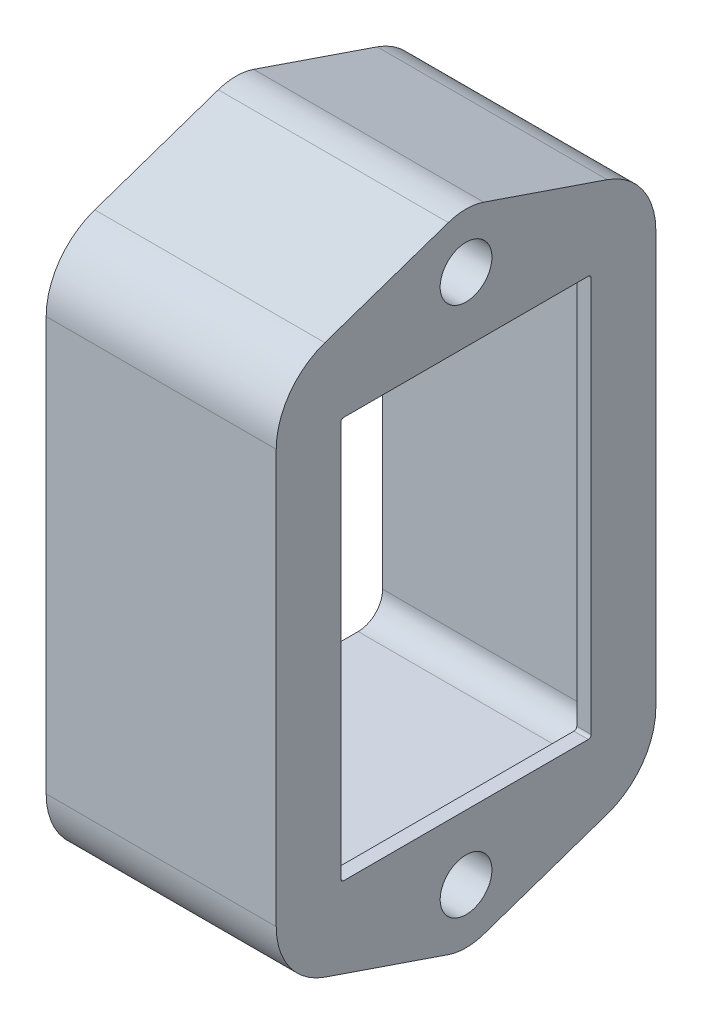
SolidWorks part; units mm, degrees
ref_plane "Alzado" through (0, 0, 0) normal (0, 0, 1) x (1, 0, 0)
ref_plane "Planta" through (0, 0, 0) normal (0, 1, 0) x (1, 0, 0)
ref_plane "Vista lateral" through (0, 0, 0) normal (1, 0, 0) x (0, 0, -1)
sketch "Croquis2" plane through (0, 0, 0) normal (1, 0, 0) x (0, 0, -1)
  line L0 (0, -55.062) -> (0, 49.3875) construction
  line L1 (-26.4, -41.4649) -> (-26.4, 16.0397)
  line L2 (-19.6372, 25.5012) -> (-2.4603, 31.3781)
  line L3 (19.6372, 25.5012) -> (2.4603, 31.3781)
  line L4 (26.4, -41.4649) -> (26.4, 16.0397)
  line L5 (19.6372, -50.9265) -> (2.4603, -56.8034)
  line L6 (20, -40.2126) -> (20, 14.7874) construction
  line L7 (17, 17.7874) -> (0, 17.7874) construction
  line L8 (0, 17.7874) -> (-17, 17.7874) construction
  line L9 (-20, 14.7874) -> (-20, -40.2126) construction
  line L10 (-17, -43.2126) -> (0, -43.2126) construction
  line L11 (0, -43.2126) -> (17, -43.2126) construction
  line L12 (20.4, -40.2126) -> (20.4, 14.7874)
  line L13 (17, 18.1874) -> (0, 18.1874)
  line L14 (0, 18.1874) -> (-17, 18.1874)
  line L15 (-20.4, 14.7874) -> (-20.4, -40.2126)
  line L16 (-17, -43.6126) -> (0, -43.6126)
  line L17 (0, -43.6126) -> (17, -43.6126)
  line L18 (-19.6372, -50.9265) -> (-2.4603, -56.8034)
  line L19 (-39.7632, -12.7126) -> (39.8458, -12.7126) construction
  circle A0 centre (0, 24.1874) radius 3.6
  arc A1 (2.4603, 31.3781) -> (-2.4603, 31.3781) centre (0, 24.1874) ccw
  arc A2 (-19.6372, 25.5012) -> (-26.4, 16.0397) centre (-16.4, 16.0397) ccw
  arc A3 (19.6372, 25.5012) -> (26.4, 16.0397) centre (16.4, 16.0397) cw
  arc A4 (20, 14.7874) -> (17, 17.7874) centre (17, 14.7874) ccw construction
  arc A5 (-17, 17.7874) -> (-20, 14.7874) centre (-17, 14.7874) ccw construction
  arc A6 (-20, -40.2126) -> (-17, -43.2126) centre (-17, -40.2126) ccw construction
  arc A7 (17, -43.2126) -> (20, -40.2126) centre (17, -40.2126) ccw construction
  arc A8 (20.4, 14.7874) -> (17, 18.1874) centre (17, 14.7874) ccw
  arc A9 (-17, 18.1874) -> (-20.4, 14.7874) centre (-17, 14.7874) ccw
  arc A10 (-20.4, -40.2126) -> (-17, -43.6126) centre (-17, -40.2126) ccw
  arc A11 (17, -43.6126) -> (20.4, -40.2126) centre (17, -40.2126) ccw
  circle A12 centre (0, -49.6126) radius 3.6
  arc A13 (2.4603, -56.8034) -> (-2.4603, -56.8034) centre (0, -49.6126) cw
  arc A14 (19.6372, -50.9265) -> (26.4, -41.4649) centre (16.4, -41.4649) ccw
  arc A15 (-19.6372, -50.9265) -> (-26.4, -41.4649) centre (-16.4, -41.4649) cw
  point P34 (-0.2444, 30.9119)
  point P36 (-20.4, -12.7126)
  point P43 (-26.4, 23.1874)
  point P53 (26.4, -12.7126)
  point P58 (-26.4, -12.7126)
  dimension "D5" = 7.2
  dimension "D2" = 4
  dimension "D7" = 10
  dimension "D3" = 6
  dimension "D4" = 6
  dimension "D6" = 5
  dimension "D1" = 0.4
extrude "Saliente-Extruir1" add sketch "Croquis2" against normal blind 30 and the other way blind 2
sketch "Croquis3" plane through (2, 0, 0) normal (1, 0, 0) x (0, 0, -1)
  line L0 (-17, -43.6126) -> (17, -43.6126) construction
  line L1 (20.4, -40.2126) -> (20.4, 14.7874) construction
  line L2 (-20.4, 14.7874) -> (-20.4, -40.2126) construction
  line L3 (17, 18.1874) -> (-17, 18.1874) construction
  line L4 (-17, -43.6126) -> (17, -43.6126)
  line L5 (20.4, -40.2126) -> (20.4, 14.7874)
  line L6 (-20.4, 14.7874) -> (-20.4, -40.2126)
  line L7 (17, 18.1874) -> (-17, 18.1874)
  line L8 (-17, -40.6126) -> (17, -40.6126)
  line L9 (17.4, -40.2126) -> (17.4, 14.7874)
  line L10 (17, 15.1874) -> (-17, 15.1874)
  line L11 (-17.4, 14.7874) -> (-17.4, -40.2126)
  arc A0 (-20.4, -40.2126) -> (-17, -43.6126) centre (-17, -40.2126) ccw construction
  arc A1 (17, -43.6126) -> (20.4, -40.2126) centre (17, -40.2126) ccw construction
  arc A2 (20.4, 14.7874) -> (17, 18.1874) centre (17, 14.7874) ccw construction
  arc A3 (-17, 18.1874) -> (-20.4, 14.7874) centre (-17, 14.7874) ccw construction
  arc A4 (-20.4, -40.2126) -> (-17, -43.6126) centre (-17, -40.2126) ccw
  arc A5 (17, -43.6126) -> (20.4, -40.2126) centre (17, -40.2126) ccw
  arc A6 (20.4, 14.7874) -> (17, 18.1874) centre (17, 14.7874) ccw
  arc A7 (-17, 18.1874) -> (-20.4, 14.7874) centre (-17, 14.7874) ccw
  arc A8 (17, -40.6126) -> (17.4, -40.2126) centre (17, -40.2126) ccw
  arc A9 (17.4, 14.7874) -> (17, 15.1874) centre (17, 14.7874) ccw
  arc A10 (-17, 15.1874) -> (-17.4, 14.7874) centre (-17, 14.7874) ccw
  arc A11 (-17.4, -40.2126) -> (-17, -40.6126) centre (-17, -40.2126) ccw
  dimension "D1" = 3
extrude "Saliente-Extruir2" add sketch "Croquis3" against normal blind 2
